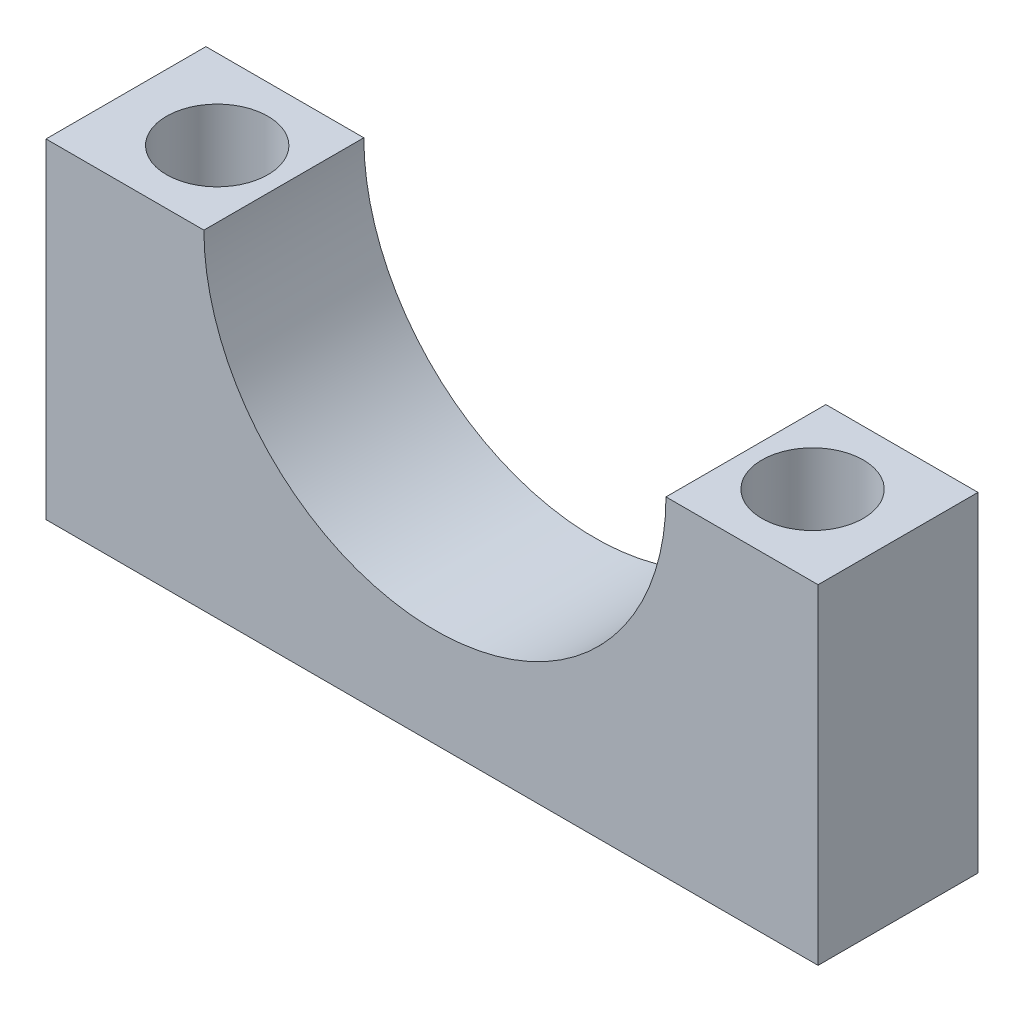
SolidWorks part; units mm, degrees
ref_plane "Front Plane" through (0, 0, 0) normal (0, 0, 1) x (1, 0, 0)
ref_plane "Top Plane" through (0, 0, 0) normal (0, 1, 0) x (1, 0, 0)
ref_plane "Right Plane" through (0, 0, 0) normal (1, 0, 0) x (0, 0, -1)
sketch "Sketch1" plane through (0, 0, 0) normal (0, 0, 1) x (1, 0, 0)
  line L0 (21.4, 11.38) -> (26.65, 11.38)
  line L1 (0, 0) -> (26.65, 0)
  line L2 (0, 0) -> (0, 11.38)
  line L3 (0, 11.38) -> (5.45, 11.38)
  line L4 (26.65, 0) -> (26.65, 11.38)
  arc A0 (5.45, 11.38) -> (21.4, 11.38) centre (13.425, 11.38) ccw
  dimension "D3" = 15.95
  dimension "D1" = 11.38
  dimension "D2" = 26.65
  dimension "D4" = 5.45
extrude "Boss-Extrude1" add sketch "Sketch1" along normal blind 5.52
sketch "Sketch2" plane through (0, 11.38, 0) normal (0, 1, 0) x (1, 0, 0)
  line L1 (0, -5.52) -> (0, 0) construction
  line L2 (13.425, -5.52) -> (13.425, 0) construction
  line L3 (5.45, -5.52) -> (21.4, -5.52) construction
  line L4 (21.4, 0) -> (5.45, 0) construction
  line L5 (1.4, -2.76) -> (1.4, -0.7659) construction
  circle A0 centre (3.15, -2.76) radius 1.75
  circle A1 centre (23.7, -2.76) radius 1.75
  point P7 (0, -2.76)
  dimension "D1" = 3.5
  dimension "D2" = 1.4
extrude "Cut-Extrude1" cut sketch "Sketch2" against normal through all
